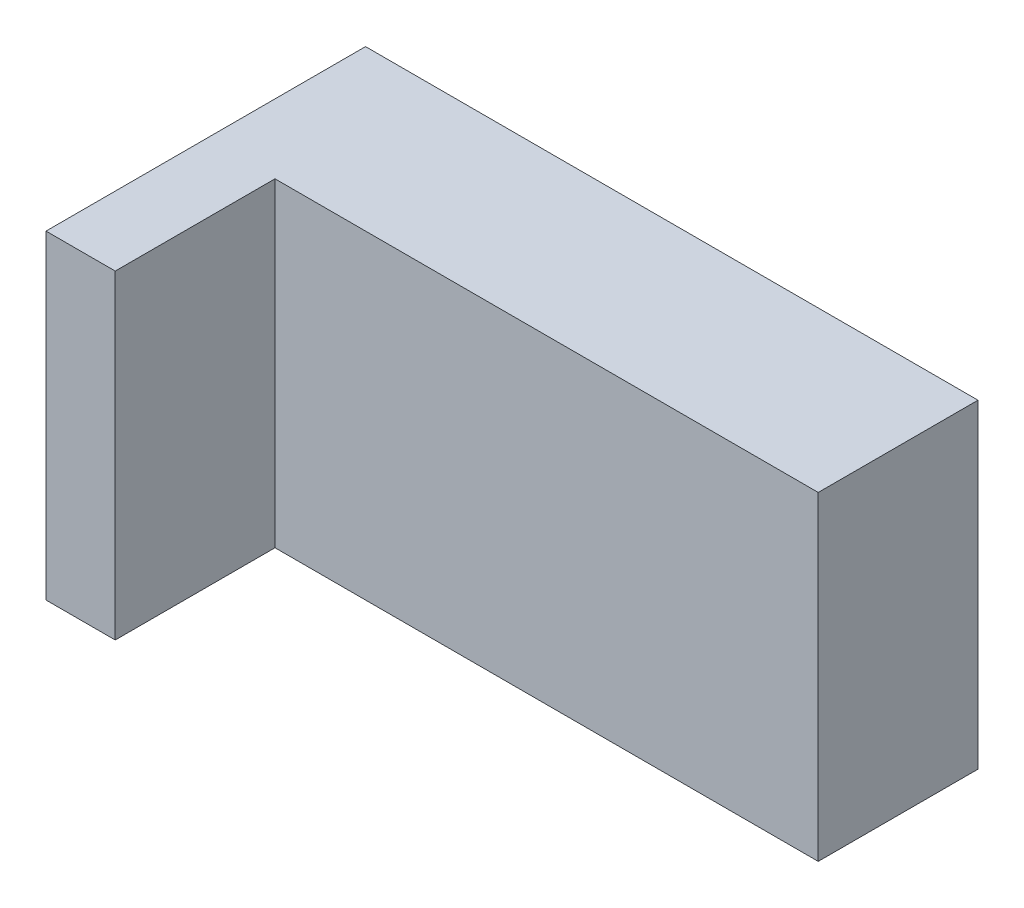
SolidWorks part; units mm, degrees
ref_plane "前视基准面" through (0, 0, 0) normal (0, 0, 1) x (1, 0, 0)
ref_plane "上视基准面" through (0, 0, 0) normal (0, 1, 0) x (1, 0, 0)
ref_plane "右视基准面" through (0, 0, 0) normal (1, 0, 0) x (0, 0, -1)
sketch "草图1" plane through (0, 0, 0) normal (0, 0, 1) x (1, 0, 0)
  line L1 (-115, 60) -> (115, 60)
  line L2 (-115, 60) -> (-115, -60)
  line L3 (-115, -60) -> (115, -60)
  line L4 (115, 60) -> (115, -60)
  line L5 (-115, 60) -> (115, -60) construction
  line L6 (-115, -60) -> (115, 60) construction
  point P0 (0, 0)
  dimension "D1" = 230
  dimension "D2" = 120
extrude "凸台-拉伸1" add sketch "草图1" along normal blind 60
sketch "草图2" plane through (0, 0, 60) normal (0, 0, 1) x (1, 0, 0)
  line L0 (-115, -60) -> (115, -60) construction
  line L1 (-115, 60) -> (-89, 60)
  line L2 (-115, 60) -> (-115, -60)
  line L3 (-115, -60) -> (-89, -60)
  line L4 (-89, 60) -> (-89, -60)
  dimension "D1" = 26
extrude "凸台-拉伸2" add sketch "草图2" along normal blind 60
